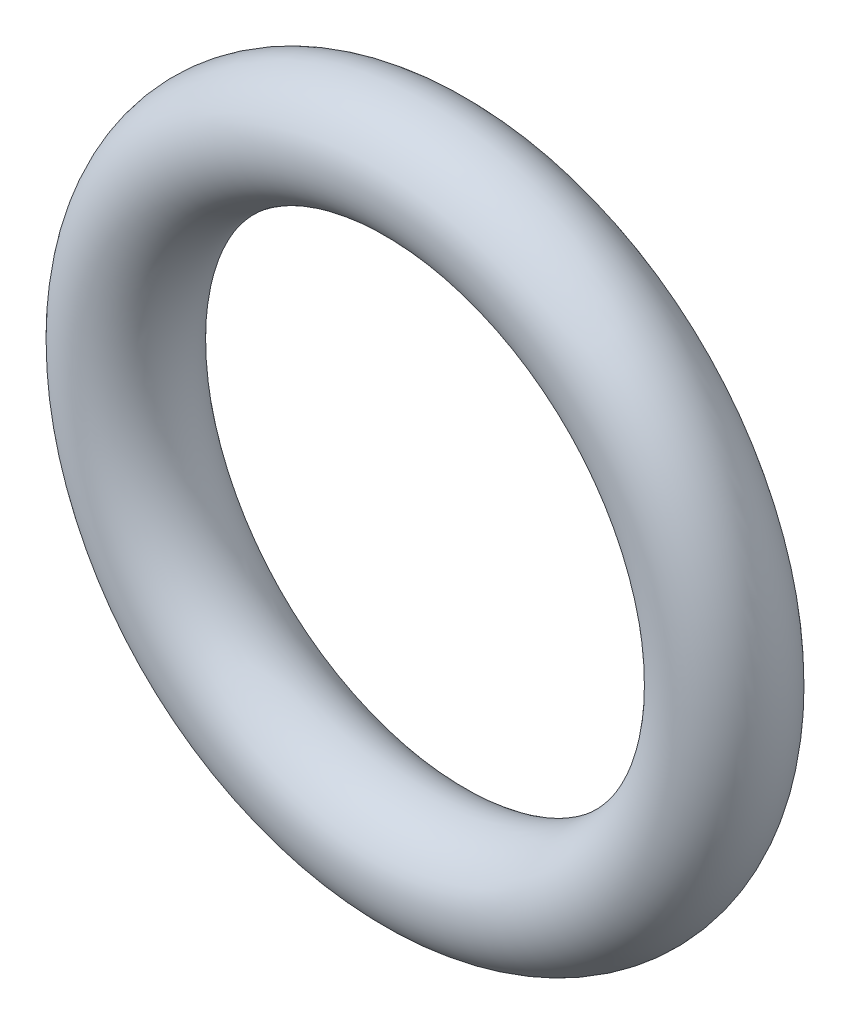
SolidWorks part; units mm, degrees
material "NBR"
ref_plane "Front" through (0, 0, 0) normal (0, 0, 1) x (1, 0, 0)
ref_plane "Top" through (0, 0, 0) normal (0, 1, 0) x (1, 0, 0)
ref_plane "Right" through (0, 0, 0) normal (1, 0, 0) x (0, 0, -1)
sketch "Sketch1" plane through (0, 0, 0) normal (1, 0, 0) x (0, -1, 0)
  line L0 (0, -0.889) -> (0, 0.889) construction
  line L2 (-6.1608, 0) -> (6.1608, 0) construction
  line L3 (-3.8227, 0) -> (3.8227, 0) construction
  circle A0 centre (4.7117, 0) radius 0.889
  point P9 (3.8227, 0)
  point P10 (5.6007, 0)
  point P13 (4.7117, 0.889)
  point P14 (4.7117, -0.889)
  dimension "Width" = 1.778
  dimension "ID" = 7.6454
revolve "Revolve1" add sketch "Sketch1" angle 360 about L0
